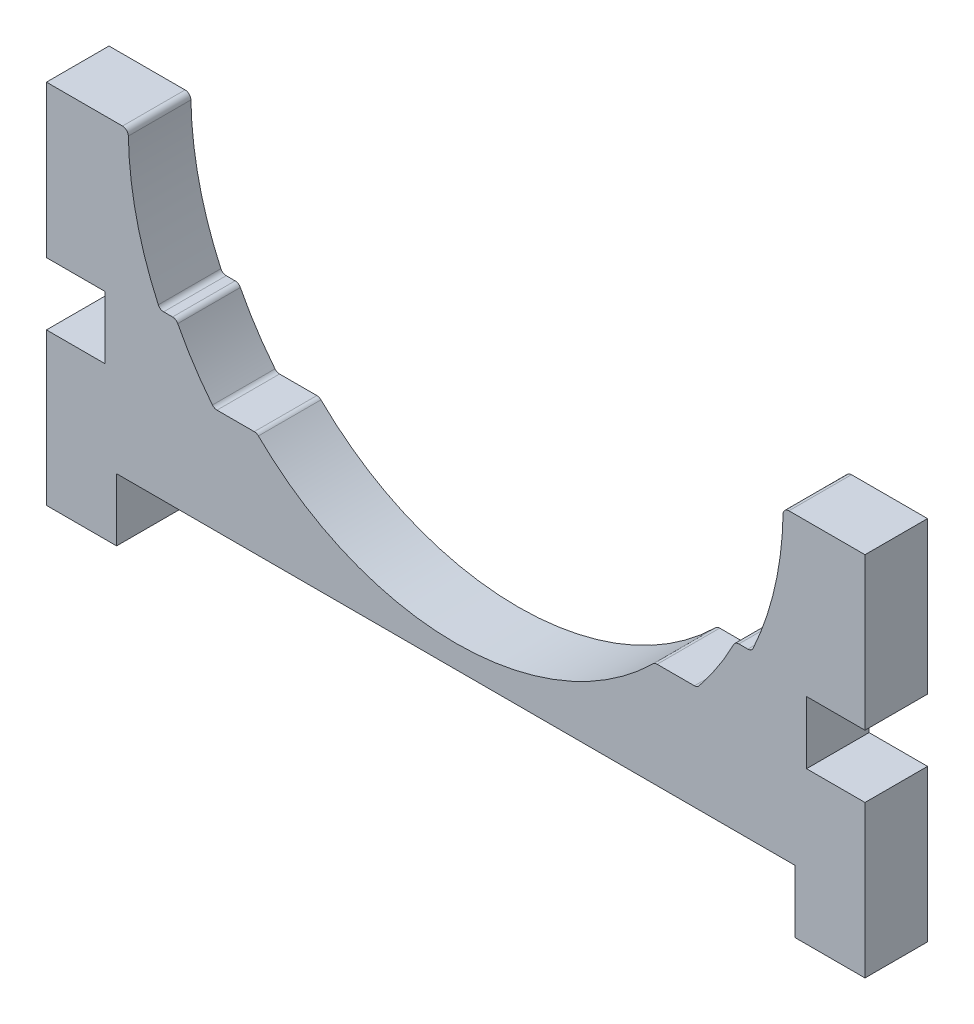
SolidWorks part; units mm, degrees
ref_plane "Front Plane" through (0, 0, 0) normal (0, 0, 1) x (1, 0, 0)
ref_plane "Top Plane" through (0, 0, 0) normal (0, 1, 0) x (1, 0, 0)
ref_plane "Right Plane" through (0, 0, 0) normal (1, 0, 0) x (0, 0, -1)
sketch "Model" plane through (0, 0, 0) normal (0, 0, 1) x (1, 0, 0)
  line L22 (0, 0) -> (0, 26) construction
  line L23 (-29, 0) -> (29, 0)
  line L24 (-35, -1.3066) -> (-35, 7.65)
  line L25 (-35, 26) -> (-28.4956, 26)
  line L26 (35, -1.3066) -> (35, 7.65)
  line L27 (35, -5.35) -> (29, -5.35)
  line L28 (28.4956, 26) -> (35, 26)
  line L29 (-35, -1.3066) -> (-35, -5.35)
  line L30 (-35, -5.35) -> (-29, -5.35)
  line L31 (-29, 0) -> (-29, -5.35)
  line L32 (29, 0) -> (29, -5.35)
  line L34 (35, -1.3066) -> (35, -5.35)
  line L35 (35, 7.65) -> (30, 7.65)
  line L36 (-35, 13) -> (-30, 13)
  line L37 (24.98, 14) -> (24.2139, 14)
  line L38 (-35, 7.65) -> (-30, 7.65)
  line L39 (-30, 13) -> (-30, 7.65)
  line L40 (30, 13) -> (30, 7.65)
  line L41 (35, 13) -> (30, 13)
  line L42 (-35, 13) -> (-35, 26)
  line L43 (35, 13) -> (35, 26)
  line L44 (-24.98, 14) -> (-24.2139, 14)
  line L45 (20.416, 9) -> (17.2249, 9)
  line L46 (-17.2249, 9) -> (-20.416, 9)
  arc A16 (-16.8742, 8.8563) -> (16.8742, 8.8563) centre (0, 26) ccw
  arc A17 (-27.9957, 25.5088) -> (-25.4342, 14.2909) centre (0, 26) ccw
  arc A18 (28.4956, 26) -> (27.9957, 25.5088) centre (28.4956, 25.5) ccw
  arc A19 (-27.9957, 25.5088) -> (-28.4956, 26) centre (-28.4956, 25.5) ccw
  arc A20 (24.98, 14) -> (25.4342, 14.2909) centre (24.98, 14.5) ccw
  arc A21 (24.2139, 14) -> (23.7696, 13.7294) centre (24.2139, 13.5) ccw
  arc A22 (-25.4342, 14.2909) -> (-24.98, 14) centre (-24.98, 14.5) ccw
  arc A23 (-23.7696, 13.7294) -> (-24.2139, 14) centre (-24.2139, 13.5) ccw
  arc A24 (20.416, 9) -> (20.8049, 9.1857) centre (20.416, 9.5) ccw
  arc A25 (17.2249, 9) -> (16.8742, 8.8563) centre (17.2249, 8.5) ccw
  arc A26 (-20.8049, 9.1857) -> (-20.416, 9) centre (-20.416, 9.5) ccw
  arc A27 (-16.8742, 8.8563) -> (-17.2249, 9) centre (-17.2249, 8.5) ccw
  arc A28 (25.4342, 14.2909) -> (27.9957, 25.5088) centre (0, 26) ccw
  arc A29 (20.8049, 9.1857) -> (23.7696, 13.7294) centre (0, 26) ccw
  arc A30 (-23.7696, 13.7294) -> (-20.8049, 9.1857) centre (0, 26) ccw
  point P115 (0, 26)
  dimension "D25" = 1
  dimension "D4" = 28
  dimension "D26" = 5.35
  dimension "D27" = 6
  dimension "D29" = 70
  dimension "D31" = 26
  dimension "D32" = 5
  dimension "D33" = 5.35
  dimension "D34" = 13
  dimension "D30" = 14
  dimension "D36" = 9
  dimension "D6" = 1.25
  dimension "D19" = 2.695
  dimension "D37" = 1.25
  dimension "D38" = 0.5
  dimension "D39" = 0.5
  dimension "D40" = 0.75
  dimension "D41" = 0.75
  dimension "D42" = 0.5
  dimension "D43" = 3.1911
extrude "Boss-Extrude1" add sketch "Model" along normal blind 5.35
equation "\"mdfthick\"=5.35"
equation "\"D26@Model\"=\"mdfthick\""
equation "\"D33@Model\"=\"mdfthick\""
equation "\"D1@Boss-Extrude1\"=\"mdfthick\""
